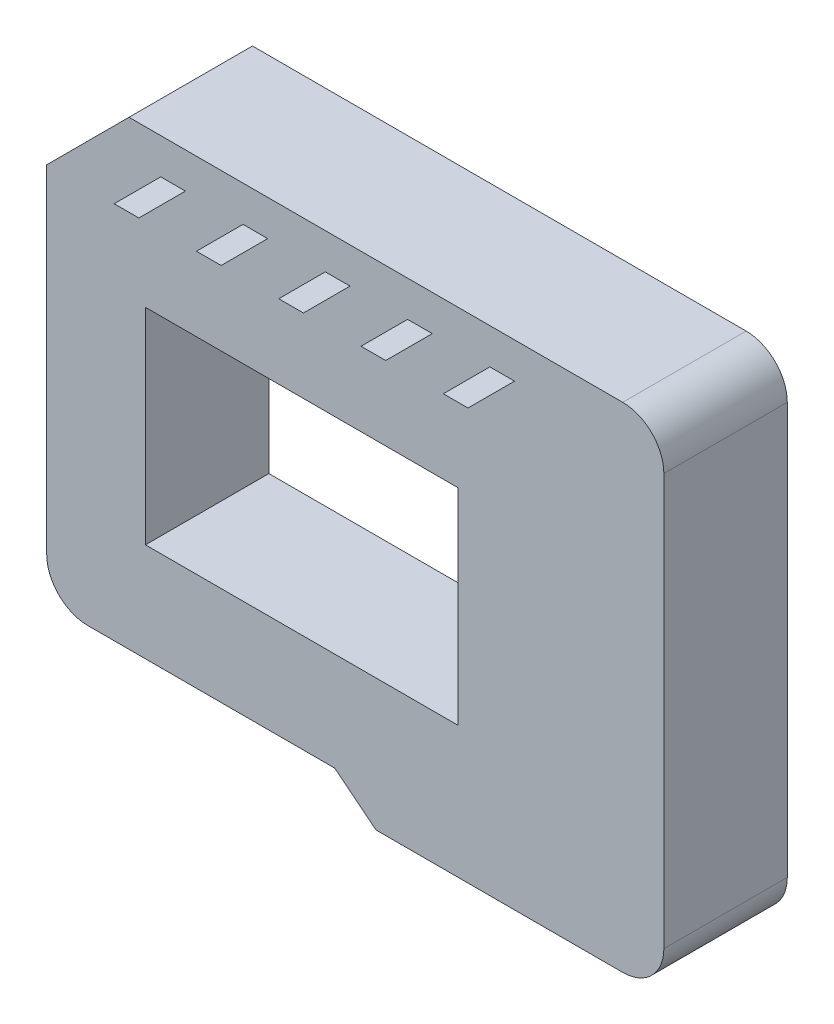
SolidWorks part; units mm, degrees
ref_plane "前视基准面" through (0, 0, 0) normal (0, 0, 1) x (1, 0, 0)
ref_plane "上视基准面" through (0, 0, 0) normal (0, 1, 0) x (1, 0, 0)
ref_plane "右视基准面" through (0, 0, 0) normal (1, 0, 0) x (0, 0, -1)
sketch "草图1" plane through (0, 0, 0) normal (0, 0, 1) x (1, 0, 0)
  line L0 (-9.9995, -56.0029) -> (25.0005, -56.0029)
  line L1 (0.0005, -0.0029) -> (65.0005, -0.0029)
  line L2 (-9.9995, -10.0029) -> (-9.9995, -56.0029)
  line L4 (65.0005, -0.0029) -> (65.0005, -60.0029)
  line L5 (25.0005, -56.0029) -> (30.0005, -60.0029)
  line L6 (30.0005, -60.0029) -> (65.0005, -60.0029)
  line L7 (-9.9995, -10.0029) -> (0.0005, -0.0029)
  dimension "D1" = 10
  dimension "D2" = 60
  dimension "D3" = 10
  dimension "D4" = 46
  dimension "D5" = 35
  dimension "D6" = 35
  dimension "D7" = 65
extrude "凸台-拉伸1" add sketch "草图1" along normal blind 15
fillet "圆角1" radius 5 3 edges at (-9.9995, -56.0029, 7.5) (65.0005, -60.0029, 7.5) (65.0005, -0.0029, 7.5)
sketch "草图3" plane through (0, 0, 15) normal (0, 0, 1) x (1, 0, 0)
  line L0 (3.8563, -4.346) -> (-1.8005, -10.0029)
  line L1 (-1.8005, -10.0029) -> (1.1995, -10.0029)
  line L2 (3.8563, -4.346) -> (6.8563, -4.346)
  line L3 (6.8563, -4.346) -> (1.1995, -10.0029)
  line L5 (16.8563, -4.346) -> (11.1995, -10.0029)
  line L6 (8.1995, -10.0029) -> (11.1995, -10.0029)
  line L7 (13.8563, -4.346) -> (8.1995, -10.0029)
  line L8 (13.8563, -4.346) -> (16.8563, -4.346)
  line L9 (26.8563, -4.346) -> (21.1995, -10.0029)
  line L10 (18.1995, -10.0029) -> (21.1995, -10.0029)
  line L11 (23.8563, -4.346) -> (18.1995, -10.0029)
  line L12 (23.8563, -4.346) -> (26.8563, -4.346)
  line L13 (36.8563, -4.346) -> (31.1995, -10.0029)
  line L14 (28.1995, -10.0029) -> (31.1995, -10.0029)
  line L15 (33.8563, -4.346) -> (28.1995, -10.0029)
  line L16 (33.8563, -4.346) -> (36.8563, -4.346)
  line L17 (46.8563, -4.346) -> (41.1995, -10.0029)
  line L18 (38.1995, -10.0029) -> (41.1995, -10.0029)
  line L19 (43.8563, -4.346) -> (38.1995, -10.0029)
  line L20 (43.8563, -4.346) -> (46.8563, -4.346)
  line L21 (-9.9995, -10.0029) -> (53.7161, -10.0029) construction
  dimension "D1" = 3
  dimension "D2" = 8
  dimension "D3" = 3
  dimension "D5" = 5
extrude "切除-拉伸1" cut sketch "草图3" against normal through all
sketch "草图4" plane through (0, 0, 15) normal (0, 0, 1) x (1, 0, 0)
  line L1 (2.0005, -19.0029) -> (40.0005, -19.0029)
  line L2 (2.0005, -19.0029) -> (2.0005, -44.0029)
  line L3 (2.0005, -44.0029) -> (40.0005, -44.0029)
  line L4 (40.0005, -19.0029) -> (40.0005, -44.0029)
  line L5 (-9.9995, -10.0029) -> (-9.9995, -51.0029) construction
  line L6 (-4.9995, -56.0029) -> (25.0005, -56.0029) construction
  dimension "D1" = 38
  dimension "D2" = 25
  dimension "D3" = 12
  dimension "D4" = 12
extrude "切除-拉伸2" cut sketch "草图4" against normal through all
